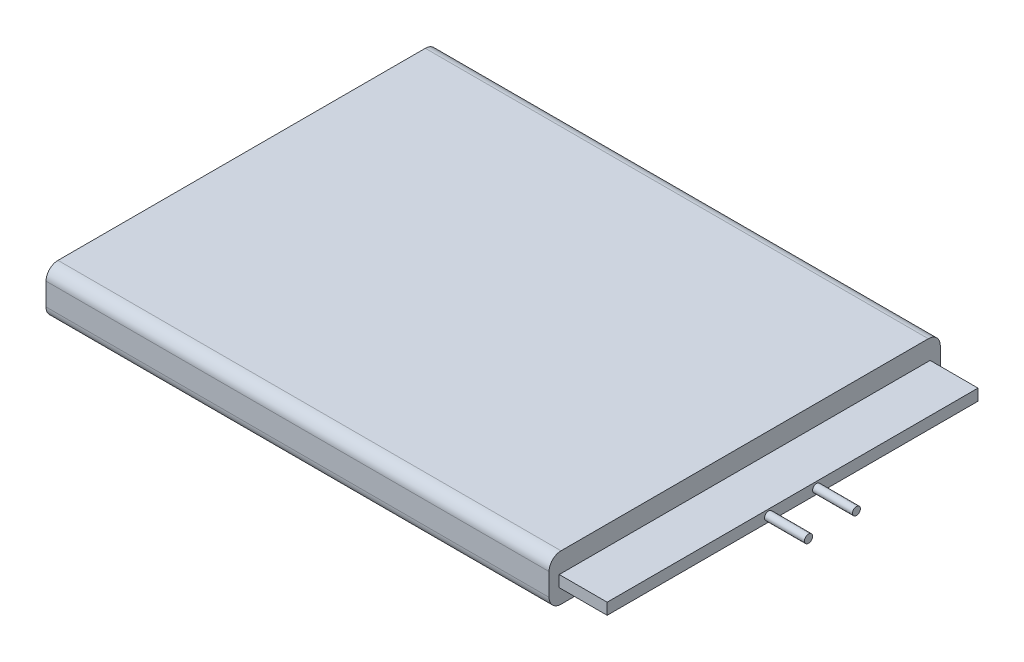
SolidWorks part; units mm, degrees
ref_plane "Alzado" through (0, 0, 0) normal (0, 0, 1) x (1, 0, 0)
ref_plane "Planta" through (0, 0, 0) normal (0, 1, 0) x (1, 0, 0)
ref_plane "Vista lateral" through (0, 0, 0) normal (1, 0, 0) x (0, 0, -1)
sketch "Croquis1" plane through (0, 0, 0) normal (0, 1, 0) x (1, 0, 0)
  line L1 (0, 0) -> (63, 0)
  line L2 (0, 0) -> (0, 49)
  line L3 (0, 49) -> (63, 49)
  line L4 (63, 0) -> (63, 49)
  dimension "D1" = 49
  dimension "D2" = 63
extrude "Saliente-Extruir1" add sketch "Croquis1" along normal blind 5.8
fillet "Redondeo1" radius 1.5 4 edges at (31.5, 0, -49) (31.5, 5.8, -49) (31.5, 0, 0) (31.5, 5.8, 0)
sketch "Croquis2" plane through (63, 0, 0) normal (1, 0, 0) x (0, 0, -1)
  line L0 (1.5, 0) -> (47.5, 0) construction
  line L1 (1.2782, 3.3359) -> (47.7218, 3.3359)
  line L2 (1.2782, 3.3359) -> (1.2782, 1.9093)
  line L3 (1.2782, 1.9093) -> (47.7218, 1.9093)
  line L4 (47.7218, 3.3359) -> (47.7218, 1.9093)
  line L5 (1.2782, 3.3359) -> (47.7218, 1.9093) construction
  line L6 (1.2782, 1.9093) -> (47.7218, 3.3359) construction
  point P0 (24.5, 2.6226)
  point P8 (24.5, 0)
extrude "Saliente-Extruir2" add sketch "Croquis2" along normal blind 6
sketch "Croquis3" plane through (69, 0, 0) normal (1, 0, 0) x (0, 0, -1)
  line L0 (1.2782, 1.9093) -> (47.7218, 1.9093) construction
  circle A0 centre (21.5, 2.6164) radius 0.51
  circle A1 centre (27.5, 2.6164) radius 0.4961
  point P6 (24.5, 1.9093)
  dimension "D1" = 3
  dimension "D2" = 6
extrude "Saliente-Extruir3" add sketch "Croquis3" along normal blind 5
ref_plane "Plano1" through (0, 0, -24.5) normal (0, 0, 1) x (1, 0, 0)
